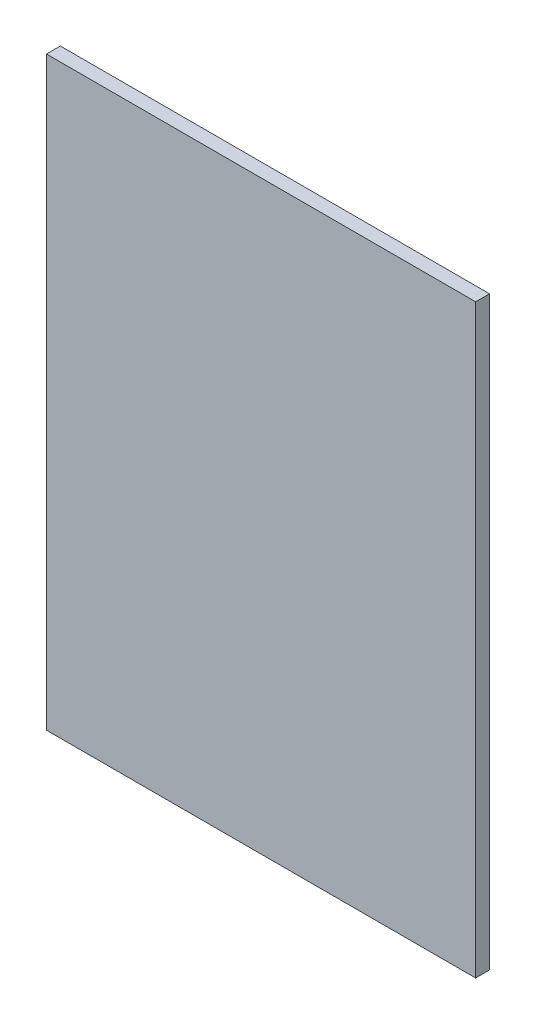
SolidWorks part; units mm, degrees
material "Sosna"
ref_plane "Płaszczyzna przednia" through (0, 0, 0) normal (0, 0, 1) x (1, 0, 0)
ref_plane "Płaszczyzna górna" through (0, 0, 0) normal (0, 1, 0) x (1, 0, 0)
ref_plane "Płaszczyzna prawa" through (0, 0, 0) normal (1, 0, 0) x (0, 0, -1)
sketch "Szkic1" plane through (0, 0, 0) normal (0, 0, 1) x (1, 0, 0)
  line L1 (0, 760) -> (557, 760)
  line L2 (0, 760) -> (0, 0)
  line L3 (0, 0) -> (557, 0)
  line L4 (557, 760) -> (557, 0)
  dimension "D1" = 760
  dimension "D2" = 557
extrude "Dodanie-wyciągnięcie1" add sketch "Szkic1" along normal blind 18 contours L2 L3 L4 L1
